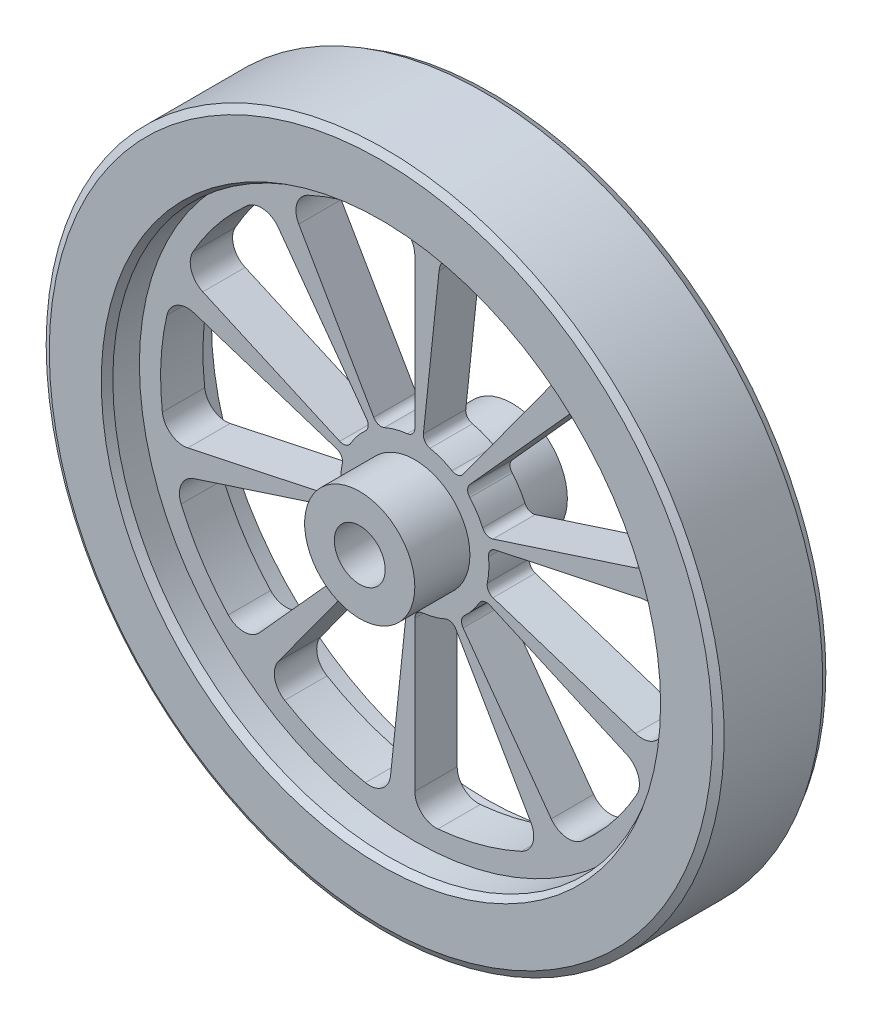
SolidWorks part; units mm, degrees
ref_plane "Front Plane" through (0, 0, 0) normal (0, 0, 1) x (1, 0, 0)
ref_plane "Top Plane" through (0, 0, 0) normal (0, 1, 0) x (1, 0, 0)
ref_plane "Right Plane" through (0, 0, 0) normal (1, 0, 0) x (0, 0, -1)
sketch "Sketch1" plane through (0, 0, 0) normal (0, 0, 1) x (1, 0, 0)
  circle A0 centre (0, 0) radius 80
  circle A1 centre (0, 0) radius 6
  dimension "D1" = 160
  dimension "D2" = 12
extrude "Boss-Extrude1" add sketch "Sketch1" along normal mid plane 26
sketch "Sketch2" plane through (0, 0, 13) normal (0, 0, 1) x (1, 0, 0)
  circle A0 centre (0, 0) radius 65
  dimension "D1" = 130
extrude "Cut-Extrude1" cut sketch "Sketch2" against normal blind 8
mirror "Mirror1" about plane through (0, 0, 0) normal (0, 0, 1) of "Cut-Extrude1"
sketch "Sketch3" plane through (0, 0, 0) normal (0, 0, 1) x (1, 0, 0)
  circle A0 centre (0, 0) radius 6 construction
  circle A1 centre (0, 0) radius 6
  circle A2 centre (0, 0) radius 13
  dimension "D1" = 26
extrude "Boss-Extrude2" add sketch "Sketch3" along normal mid plane 36
chamfer "Chamfer1" distance 1 angle 60 2 edges at (80, 0, -13) (80, 0, 13)
sketch "Sketch4" plane through (0, 0, 5) normal (0, 0, 1) x (1, 0, 0)
  line L0 (0, 17.5) -> (0, 60) construction
  line L1 (0, 0) -> (-30, 51.9615) construction
  line L2 (0, 54.7723) -> (0, 19.3972)
  line L3 (-9.6986, 16.7984) -> (-27.3861, 47.4342)
  arc A0 (-1.7949, 17.4077) -> (-7.1495, 15.973) centre (0, 0) ccw
  arc A1 (-5.4545, 59.7516) -> (-25.152, 54.4736) centre (0, 0) ccw
  arc A3 (-5.4545, 59.7516) -> (0, 54.7723) centre (-5, 54.7723) cw
  arc A4 (-27.3861, 47.4342) -> (-25.152, 54.4736) centre (-23.056, 49.9342) cw
  arc A5 (-1.7949, 17.4077) -> (0, 19.3972) centre (-2, 19.3972) ccw
  arc A6 (-9.6986, 16.7984) -> (-7.1495, 15.973) centre (-7.9665, 17.7984) ccw
  point P17 (-8.75, 15.1554)
  dimension "D1" = 120
  dimension "D2" = 35
  dimension "D4" = 5
  dimension "D5" = 2
  dimension "D3" = 30
extrude "Cut-Extrude2" cut sketch "Sketch4" against normal through all
pattern_circular "CirPattern1" count 10 over 360 about axis through (0, 0, 0) along (0, 0, 1) of "Cut-Extrude2"
